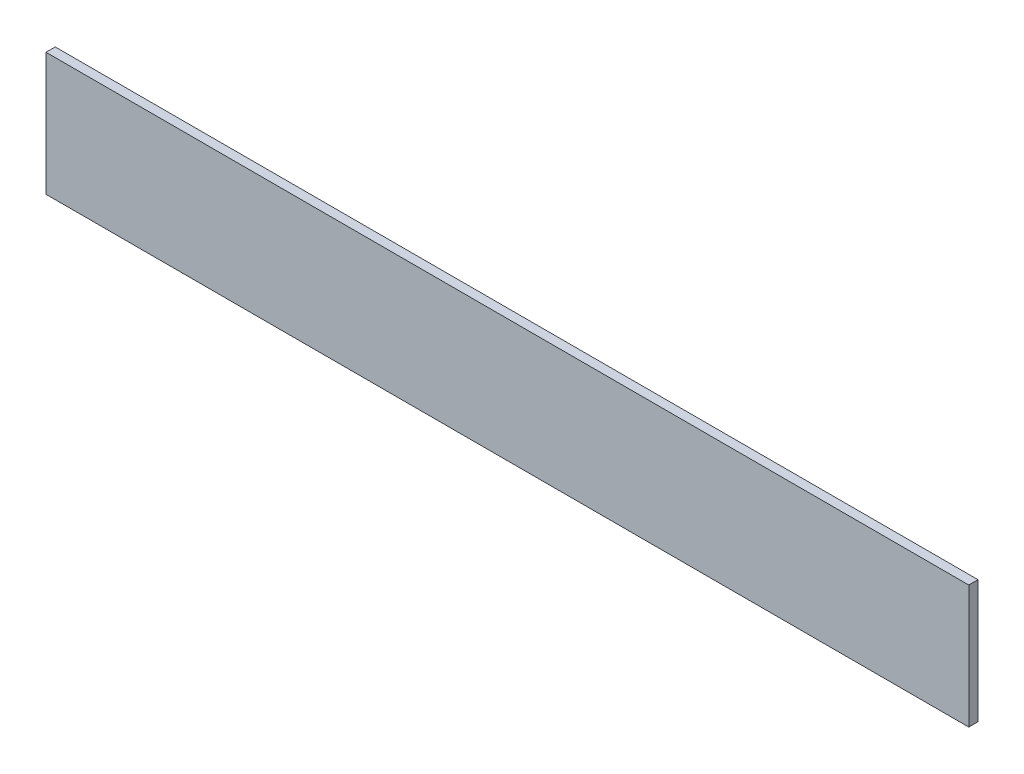
SolidWorks part; units mm, degrees
ref_plane "Front Plane" through (0, 0, 0) normal (0, 0, 1) x (1, 0, 0)
ref_plane "Top Plane" through (0, 0, 0) normal (0, 1, 0) x (1, 0, 0)
ref_plane "Right Plane" through (0, 0, 0) normal (1, 0, 0) x (0, 0, -1)
sketch "Sketch1" plane through (0, 0, 0) normal (0, 0, 1) x (1, 0, 0)
  line L1 (0, 0) -> (300, 0)
  line L2 (0, 0) -> (0, 40)
  line L3 (0, 40) -> (300, 40)
  line L4 (300, 0) -> (300, 40)
  dimension "D1" = 300
  dimension "D2" = 40
extrude "Boss-Extrude1" add sketch "Sketch1" along normal blind 3
